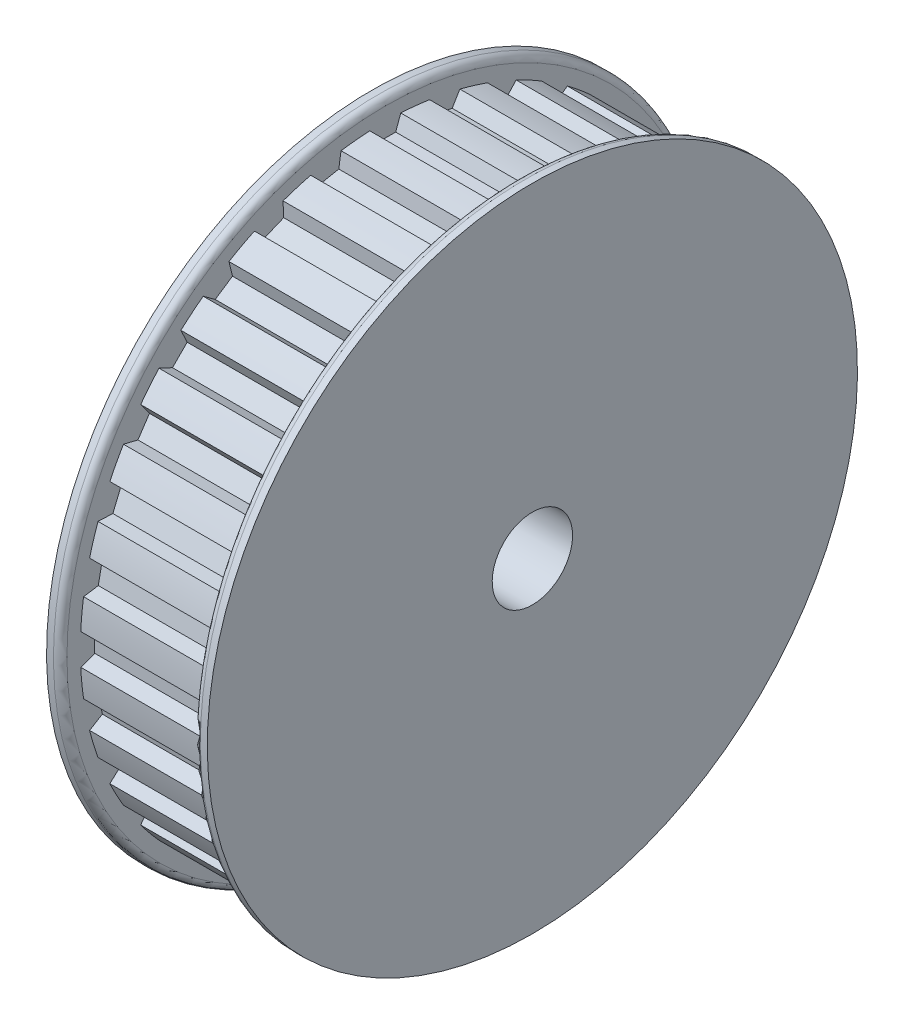
SolidWorks part; units mm, degrees
ref_plane "Front Plane" through (0, 0, 0) normal (0, 0, 1) x (1, 0, 0)
ref_plane "Top Plane" through (0, 0, 0) normal (0, 1, 0) x (1, 0, 0)
ref_plane "Right Plane" through (0, 0, 0) normal (1, 0, 0) x (0, 0, -1)
sketch "Sketch2" plane through (0, 0, 0) normal (1, 0, 0) x (0, 0, -1)
  line L3 (0, 0) -> (0, 45.9298) construction
  line L6 (0, -47.8348) -> (0, -48.514) construction
  line L7 (-2.3241, 47.7783) -> (-1.6406, 45.9005)
  line L8 (2.3241, 47.7783) -> (1.6406, 45.9005)
  line L9 (-2.3241, 47.7783) -> (-2.4457, 48.1123)
  line L10 (2.3241, 47.7783) -> (2.4457, 48.1123)
  line L12 (-1.6406, 45.9005) -> (1.6406, 45.9005)
  line L14 (0, 47.8348) -> (0, 48.514) construction
  line L15 (0, 0) -> (0, -3.556) construction
  circle A0 centre (0, 0) radius 48.514 construction
  circle A1 centre (0, 0) radius 45.9298 construction
  circle A2 centre (0, 0) radius 47.8348 construction
  arc A7 (2.4457, 48.1123) -> (-2.4457, 48.1123) centre (0, 0) ccw
  point P5 (0, 48.1744)
  dimension "D1" = 40
  dimension "PD" = 97.028
  dimension "D2" = 95.6696
  dimension "bt" = 4.6482
  dimension "hs" = 3.556
  dimension "ht" = 1.905
sketch "Sketch1" plane through (0, 0, 0) normal (0, 0, 1) x (1, 0, 0)
  line L0 (-19.05, 0) -> (19.05, 0) construction
  line L1 (-19.05, 6.35) -> (19.05, 6.35)
  line L2 (-19.05, 6.35) -> (-19.05, 33.3375)
  line L3 (-6.35, 51.3588) -> (-5.2578, 51.3588)
  line L4 (-4.191, 48.514) -> (-4.191, 50.292)
  line L5 (-4.191, 52.07) -> (-4.191, 48.514) construction
  line L6 (-4.191, 48.514) -> (16.891, 48.514)
  line L7 (16.891, 48.514) -> (16.891, 50.292)
  line L8 (16.891, 48.514) -> (19.05, 48.514) construction
  line L9 (17.9578, 51.3588) -> (19.05, 51.3588)
  line L10 (19.05, 51.3588) -> (19.05, 6.35)
  line L11 (-6.35, 33.3375) -> (19.05, 33.3375) construction
  line L12 (-12.7, 33.3375) -> (-12.7, 6.35) construction
  line L13 (-6.35, 51.3588) -> (-6.35, 33.3375)
  line L14 (-6.35, 33.3375) -> (-19.05, 33.3375)
  line L15 (6.35, 33.3375) -> (6.35, 48.514) construction
  arc A0 (16.891, 50.292) -> (17.9578, 51.3588) centre (17.9578, 50.292) cw
  arc A1 (-4.191, 50.292) -> (-5.2578, 51.3588) centre (-5.2578, 50.292) ccw
  dimension "Bore Size" = 12.7
  dimension "D2" = 97.028
  dimension "Overall Width" = 38.1
  dimension "Inside Width" = 21.082
  dimension "Outside Width" = 25.4
  dimension "Hub Dia" = 66.675
  dimension "OD" = 102.7176
  dimension "D3" = 3.556
  dimension "D4" = 1.778
revolve "Revolve1" add sketch "Sketch1" angle 360 mid plane about L0
sketch "Sketch4" plane through (-4.191, 0, 0) normal (1, 0, 0) x (0, 0, -1)
  circle A0 centre (0, 0) radius 48.1744
  circle A2 centre (0, 0) radius 48.514
  circle A3 centre (0, 0) radius 48.514 construction
extrude "Cut-Extrude2" cut sketch "Sketch4" along normal up to surface (21.082 mm away) up to face at (16.891, -48.514, 0)
sketch "Sketch3" plane through (-4.191, 0, 0) normal (1, 0, 0) x (0, 0, -1)
  line L2 (-2.3241, 47.7783) -> (-1.6406, 45.9005) construction
  line L3 (-1.6406, 45.9005) -> (1.6406, 45.9005) construction
  line L4 (2.3241, 47.7783) -> (1.6406, 45.9005) construction
  line L5 (-2.4457, 48.1123) -> (-1.6406, 45.9005)
  line L6 (-1.6406, 45.9005) -> (1.6406, 45.9005)
  line L7 (2.4457, 48.1123) -> (1.6406, 45.9005)
  arc A1 (2.4457, 48.1123) -> (-2.4457, 48.1123) centre (0, 0) ccw construction
  arc A2 (2.4457, 48.1123) -> (-2.4457, 48.1123) centre (0, 0) ccw
extrude "Cut-Extrude1" cut sketch "Sketch3" along normal up to surface (21.082 mm away)
pattern_circular "CirPattern1" count 32 over 360 about axis through (0, 0, 0) along (1, 0, 0) of "Cut-Extrude1"
sketch "Sketch5" plane through (0, 0, 0) normal (0, 0, 1) x (1, 0, 0)
  line L1 (16.891, 50.292) -> (16.891, -50.292) construction
  point P0 (16.891, 0)
sketch "Sketch6" plane through (0, 0, 0) normal (0, 1, 0) x (1, 0, 0)
  line L0 (-19.05, 0) -> (-15.875, 0) construction
  line L1 (-19.05, 51.3588) -> (-19.05, -51.3588) construction
  line L2 (-6.35, 0) -> (-9.525, 0) construction
  line L4 (-6.35, 51.3588) -> (-6.35, -51.3588) construction
  circle A0 centre (-12.7, 0) radius 3.175
  dimension "D1" = 6.35
extrude "Cut-Extrude3" cut sketch "Sketch6" along normal through all
sketch "Sketch7" plane through (0, 0, 0) normal (0, 0, 1) x (1, 0, 0)
  line L0 (-15.621, 33.3375) -> (-12.7, 33.3375)
  line L1 (-15.875, 33.0835) -> (-15.875, 6.985)
  line L2 (-15.875, 6.985) -> (-15.621, 6.731)
  line L3 (-15.621, 6.731) -> (-12.7, 6.731)
  line L4 (-12.7, 6.731) -> (-12.7, 33.3375) construction
  line L5 (-6.35, 33.3375) -> (-19.05, 33.3375) construction
  line L6 (-15.875, 33.0835) -> (-15.621, 33.3375)
  line L8 (-12.7, 33.3375) -> (-12.7, 6.731)
  point P0 (-15.875, 33.3375)
  point P4 (-15.875, 6.731)
  dimension "D1" = 6.35
  dimension "D2" = 0.381
revolve "Revolve2" add sketch "Sketch7" angle 360 mid plane about L4
sketch "Sketch8" plane through (0, 33.3375, 0) normal (0, 1, 0) x (1, 0, 0)
  line L1 (-12.7, 1.8331) -> (-14.2875, 0.9165)
  line L2 (-14.2875, 0.9165) -> (-14.2875, -0.9165)
  line L3 (-14.2875, -0.9165) -> (-12.7, -1.8331)
  line L4 (-12.7, -1.8331) -> (-11.1125, -0.9165)
  line L5 (-11.1125, -0.9165) -> (-11.1125, 0.9165)
  line L6 (-11.1125, 0.9165) -> (-12.7, 1.8331)
  circle A0 centre (-12.7, 0) radius 1.5875 construction
  dimension "D1" = 3.175
extrude "Cut-Extrude4" cut sketch "Sketch8" against normal blind 2.032
pattern_circular "CirPattern2" count 2 over 90 about axis through (-19.05, 0, 0) along (-1, 0, 0) of "Cut-Extrude3"
pattern_circular "CirPattern3" count 2 over 90 about axis through (0, 0, 0) along (1, 0, 0) of bodies 107
equation "\"D2@Sketch1\" = \"PD@Sketch2\""
equation "\"D3@Sketch1\" = \"hs@Sketch2\""
equation "\"D4@Sketch1\" = \"D3@Sketch1\"/2"
equation "\"D2@Sketch2\" = \"PD@Sketch2\"*.986"
